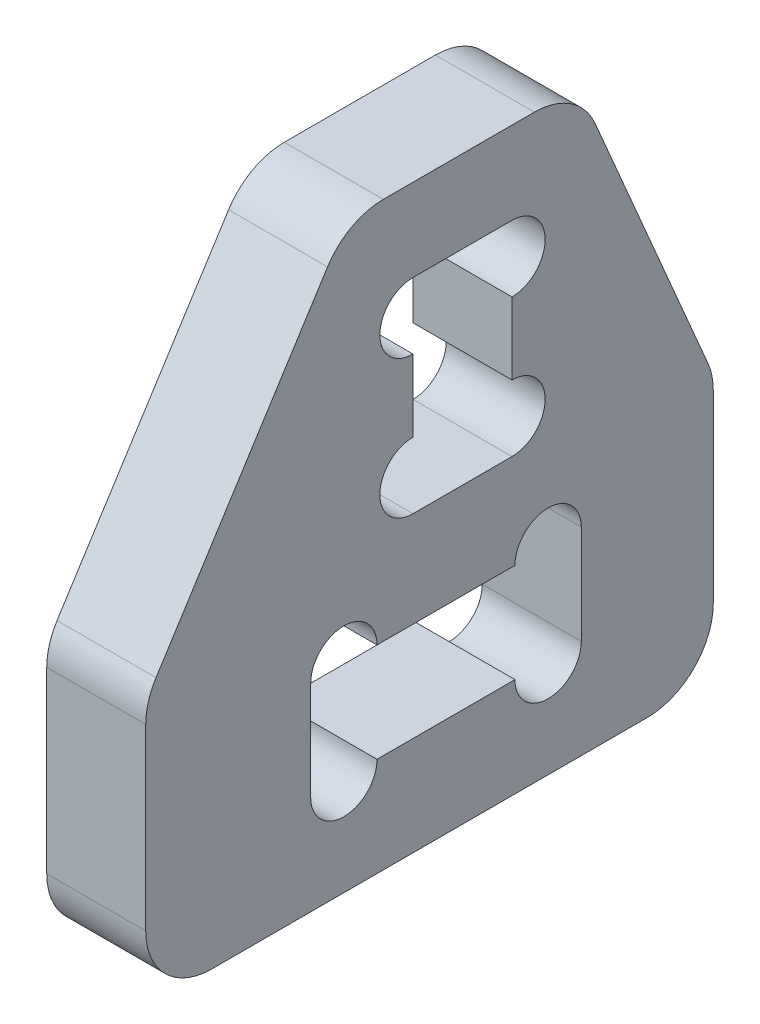
SolidWorks part; units mm, degrees
material "Thornel Mat VMA"
ref_plane "前视基准面" through (0, 0, 0) normal (0, 0, 1) x (1, 0, 0)
ref_plane "上视基准面" through (0, 0, 0) normal (0, 1, 0) x (1, 0, 0)
ref_plane "右视基准面" through (0, 0, 0) normal (1, 0, 0) x (0, 0, -1)
sketch "草图1" plane through (0, 0, 0) normal (1, 0, 0) x (0, 0, -1)
  line L0 (-3.5, 5.6) -> (3.5, 5.6)
  line L1 (1.5, -3.1) -> (-1.5, -3.1)
  line L2 (1.5, -3.1) -> (1.5, 3.1)
  line L3 (1.5, 3.1) -> (-1.5, 3.1)
  line L4 (-1.5, -3.1) -> (-1.5, 3.1)
  line L5 (1.5, -3.1) -> (-1.5, 3.1) construction
  line L6 (1.5, 3.1) -> (-1.5, -3.1) construction
  line L7 (-4.6, -9) -> (3.6, -9)
  line L8 (-4.6, -9) -> (-4.6, -6)
  line L9 (-4.6, -6) -> (3.6, -6)
  line L10 (3.6, -9) -> (3.6, -6)
  line L11 (-4.6, -9) -> (3.6, -6) construction
  line L12 (-4.6, -6) -> (3.6, -9) construction
  line L13 (3.5, 5.6) -> (7.6, -4)
  line L14 (7.6, -4) -> (7.6, -12)
  line L15 (7.6, -12) -> (-9.6, -12)
  line L16 (-9.6, -12) -> (-9.6, -4)
  line L17 (-9.6, -4) -> (-3.5, 5.6)
  line L18 (0, 0) -> (0, 2.2873) construction
  line L19 (-0.5, -7.5) -> (-0.5, -4.461) construction
  circle A0 centre (1.5, -2.095) radius 1.005
  circle A1 centre (-1.5, -2.095) radius 1.005
  circle A2 centre (-1.5, 2.095) radius 1.005
  circle A3 centre (1.5, 2.095) radius 1.005
  circle A4 centre (-3.595, -6) radius 1.005
  circle A5 centre (-3.595, -9) radius 1.005
  circle A6 centre (2.595, -6) radius 1.005
  circle A7 centre (2.595, -9) radius 1.005
  point P0 (0, 0)
  point P6 (-0.5, -7.5)
  dimension "D6" = 2.01
  dimension "D1" = 0.5
  dimension "D2" = 3
  dimension "D3" = 6.2
  dimension "D4" = 8.2
  dimension "D5" = 7.5
  dimension "D7" = 3.5
  dimension "D8" = 4
  dimension "D9" = 3
  dimension "D10" = 2
  dimension "D11" = 2.5
  dimension "D12" = 5
extrude "凸台-拉伸1" add sketch "草图1" along normal blind 3 contours L17 L16 L15 L14 L13 L0 A7 L7 A5 L8 A4 L9 A6 L10 A3 L2 A0 L1 A1 L4 A2 L3
fillet "圆角1" radius 2 6 edges at (1.5, 5.6, 3.5) (1.5, -4, -7.6) (1.5, -12, -7.6) (1.5, -12, 9.6) (1.5, -4, 9.6) (1.5, 5.6, -3.5)
